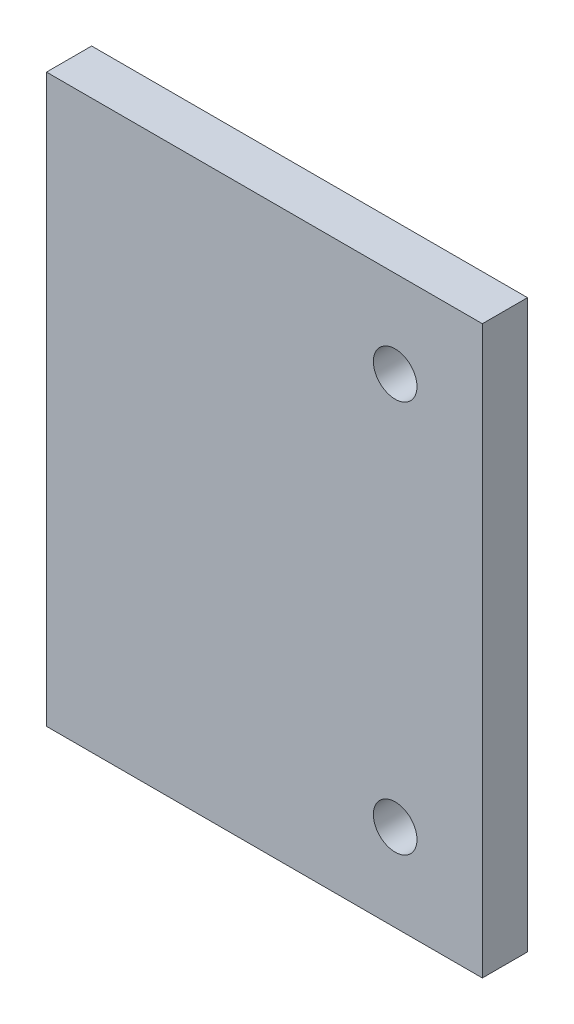
SolidWorks part; units mm, degrees
material "6061 Alloy"
ref_plane "X-Y Datum" through (0, 0, 0) normal (0, 0, 1) x (1, 0, 0)
ref_plane "X-Z Datum" through (0, 0, 0) normal (0, 1, 0) x (1, 0, 0)
ref_plane "Y-Z Datum" through (0, 0, 0) normal (1, 0, 0) x (0, 0, -1)
sketch "Sketch1" plane through (0, 0, 0) normal (0, 0, 1) x (1, 0, 0)
  line L1 (-31.75, -41.275) -> (31.75, -41.275)
  line L2 (-31.75, -41.275) -> (-31.75, 41.275)
  line L3 (-31.75, 41.275) -> (31.75, 41.275)
  line L4 (31.75, -41.275) -> (31.75, 41.275)
  line L5 (-31.75, -41.275) -> (31.75, 41.275) construction
  line L6 (-31.75, 41.275) -> (31.75, -41.275) construction
  point P0 (0, 0)
  dimension "D1" = 82.55
  dimension "D2" = 63.5
extrude "Boss-Extrude1" add sketch "Sketch1" along normal mid plane 6.5786
sketch "Sketch2" plane through (0, 0, 3.2893) normal (0, 0, 1) x (1, 0, 0)
  line L0 (31.75, -41.275) -> (31.75, 41.275) construction
  line L1 (31.75, 41.275) -> (-31.75, 41.275) construction
  line L2 (-31.75, -41.275) -> (31.75, -41.275) construction
  point P0 (19.05, 28.575)
  point P1 (19.05, -28.575)
  dimension "D1" = 12.7
  dimension "D2" = 12.7
  dimension "D3" = 12.7
  dimension "D4" = 12.7
hole_wizard "#97 (0.25) Diameter Hole2" positions "3DSketch1" profile "Sketch3" hole size "#97" standard "ANSI Inch" end condition through all
sketch3d "3DSketch1"
  point P0 (19.05, 28.575, 3.2893)
  point P3 (19.05, -28.575, 3.2893)
sketch "Sketch3" plane through (19.05, 28.575, 3.2893) normal (1, 0, 0) x (0, -1, 0)
  line L0 (0, 0) -> (0, 6.5786)
  line L1 (0, 6.5786) -> (3.175, 6.5786)
  line L2 (3.175, 6.5786) -> (3.175, 0)
  line L5 (3.175, 0) -> (0, 0)
  line L11 (0, -6.35) -> (0, 107.95) construction
  dimension "Thru Hole Dia." = 6.35
  dimension "Thru Hole Depth" = 6.5786
